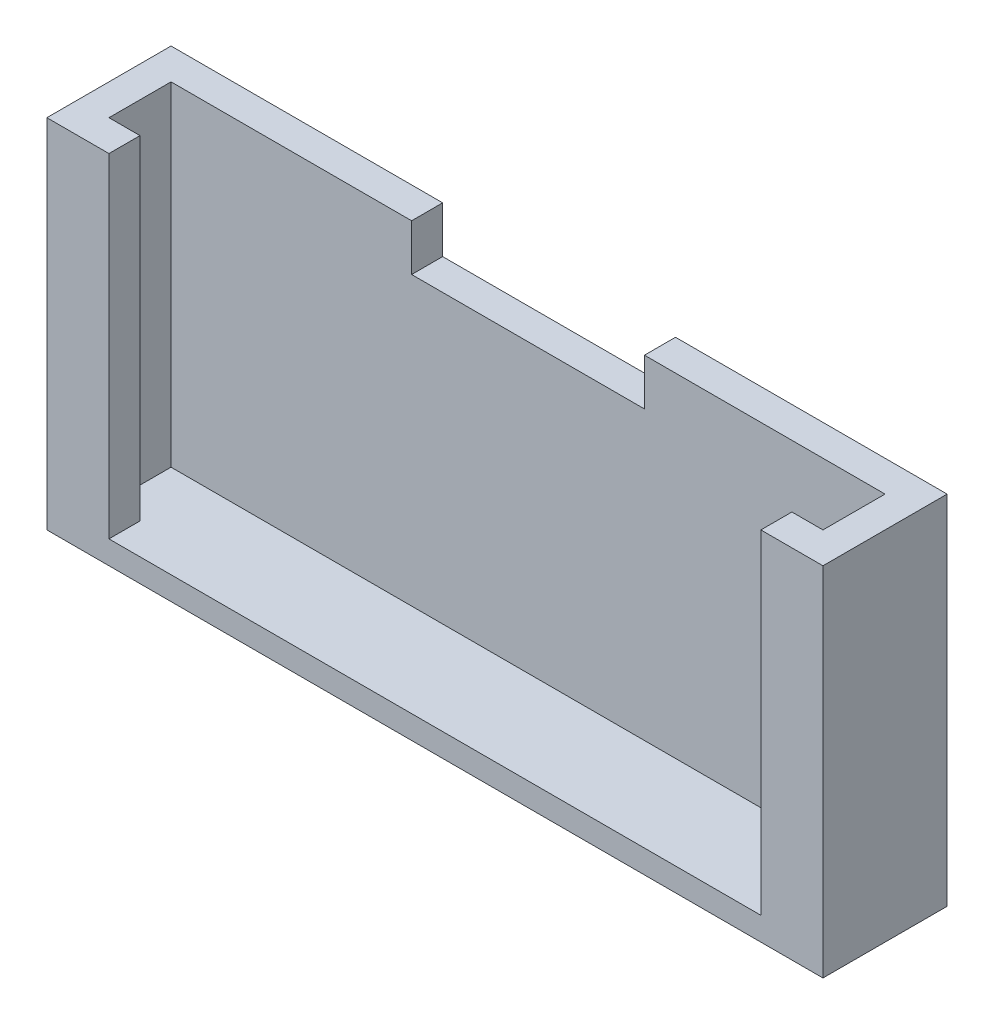
SolidWorks part; units mm, degrees
ref_plane "Front Plane" through (0, 0, 0) normal (0, 0, 1) x (1, 0, 0)
ref_plane "Top Plane" through (0, 0, 0) normal (0, 1, 0) x (1, 0, 0)
ref_plane "Right Plane" through (0, 0, 0) normal (1, 0, 0) x (0, 0, -1)
sketch "Sketch1" plane through (0, 0, 0) normal (0, 0, 1) x (1, 0, 0)
  line L1 (-25, 11.5) -> (25, 11.5)
  line L2 (-25, 11.5) -> (-25, -11.5)
  line L3 (-25, -11.5) -> (25, -11.5)
  line L4 (25, 11.5) -> (25, -11.5)
  line L5 (-25, 11.5) -> (25, -11.5) construction
  line L6 (-25, -11.5) -> (25, 11.5) construction
  point P0 (0, 0)
  dimension "D1" = 50
  dimension "D2" = 23
extrude "Boss-Extrude1" add sketch "Sketch1" along normal blind 2
sketch "Sketch2" plane through (0, 0, 2) normal (0, 0, 1) x (1, 0, 0)
  line L1 (-25, 11.5) -> (25, 11.5)
  line L2 (-25, 11.5) -> (-25, -11.5)
  line L3 (-25, -11.5) -> (25, -11.5)
  line L4 (25, 11.5) -> (25, -11.5)
extrude "Boss-Extrude2" add sketch "Sketch2" along normal blind 6
sketch "Sketch3" plane through (0, 0, 8) normal (0, 0, 1) x (1, 0, 0)
  line L1 (-23, 10) -> (23, 10)
  line L2 (-23, 10) -> (-23, -10)
  line L3 (-23, -10) -> (23, -10)
  line L4 (23, 10) -> (23, -10)
  line L5 (-23, 10) -> (23, -10) construction
  line L6 (-23, -10) -> (23, 10) construction
  point P0 (0, 0)
  dimension "D1" = 46
  dimension "D2" = 20
extrude "Cut-Extrude1" cut sketch "Sketch3" against normal blind 4
sketch "Sketch4" plane through (0, 10, 0) normal (0, -1, 0) x (1, 0, 0)
  line L1 (-23, 8) -> (23, 8)
  line L2 (-23, 8) -> (-23, 4)
  line L3 (-23, 4) -> (23, 4)
  line L4 (23, 8) -> (23, 4)
extrude "Cut-Extrude2" cut sketch "Sketch4" against normal blind 4
sketch "Sketch5" plane through (0, 0, 4) normal (0, 0, 1) x (1, 0, 0)
  line L1 (-23, 11.5) -> (23, 11.5)
  line L2 (-23, 11.5) -> (-23, -10)
  line L3 (-23, -10) -> (23, -10)
  line L4 (23, 11.5) -> (23, -10)
extrude "Cut-Extrude3" cut sketch "Sketch5" against normal blind 2
sketch "Sketch6" plane through (23, 0, 0) normal (-1, 0, 0) x (0, 0, 1)
  line L0 (2, -10) -> (8, -10) construction
  line L1 (2, 11.5) -> (6, 11.5)
  line L2 (2, 11.5) -> (2, -10)
  line L3 (2, -10) -> (6, -10)
  line L4 (6, 11.5) -> (6, -10)
  line L6 (6, 11.5) -> (8, 11.5)
  line L7 (6, 11.5) -> (6, -10)
  line L8 (6, -10) -> (8, -10)
  line L9 (8, 11.5) -> (8, -10)
  line M5 (8, -10) -> (8, 11.5)
  line M6 (8, 11.5) -> (2, 11.5)
  line M8 (2, -10) -> (8, -10)
  dimension "D1" = 4
extrude "Boss-Extrude3" add sketch "Sketch6" along normal blind 2 contours L4 M6 M8 M5
sketch "Sketch7" plane through (-23, 0, 0) normal (1, 0, 0) x (0, 0, -1)
  line L0 (-2, -10) -> (-8, -10) construction
  line L1 (-8, 11.5) -> (-6, 11.5)
  line L2 (-8, 11.5) -> (-8, -10)
  line L3 (-8, -10) -> (-6, -10)
  line L4 (-6, 11.5) -> (-6, -10)
  dimension "D1" = 2
extrude "Boss-Extrude4" add sketch "Sketch7" along normal blind 2
sketch "Sketch8" plane through (0, 0, 2) normal (0, 0, 1) x (1, 0, 0)
  line L0 (-23, 11.5) -> (23, 11.5) construction
  line L2 (-7.5, 14.5) -> (7.5, 14.5)
  line L3 (-7.5, 14.5) -> (-7.5, 8.5)
  line L4 (-7.5, 8.5) -> (7.5, 8.5)
  line L5 (7.5, 14.5) -> (7.5, 8.5)
  line L6 (-7.5, 14.5) -> (7.5, 8.5) construction
  line L7 (-7.5, 8.5) -> (7.5, 14.5) construction
  point P4 (0, 11.5)
  dimension "D1" = 15
  dimension "D2" = 6
extrude "Cut-Extrude5" cut sketch "Sketch8" against normal blind 2
